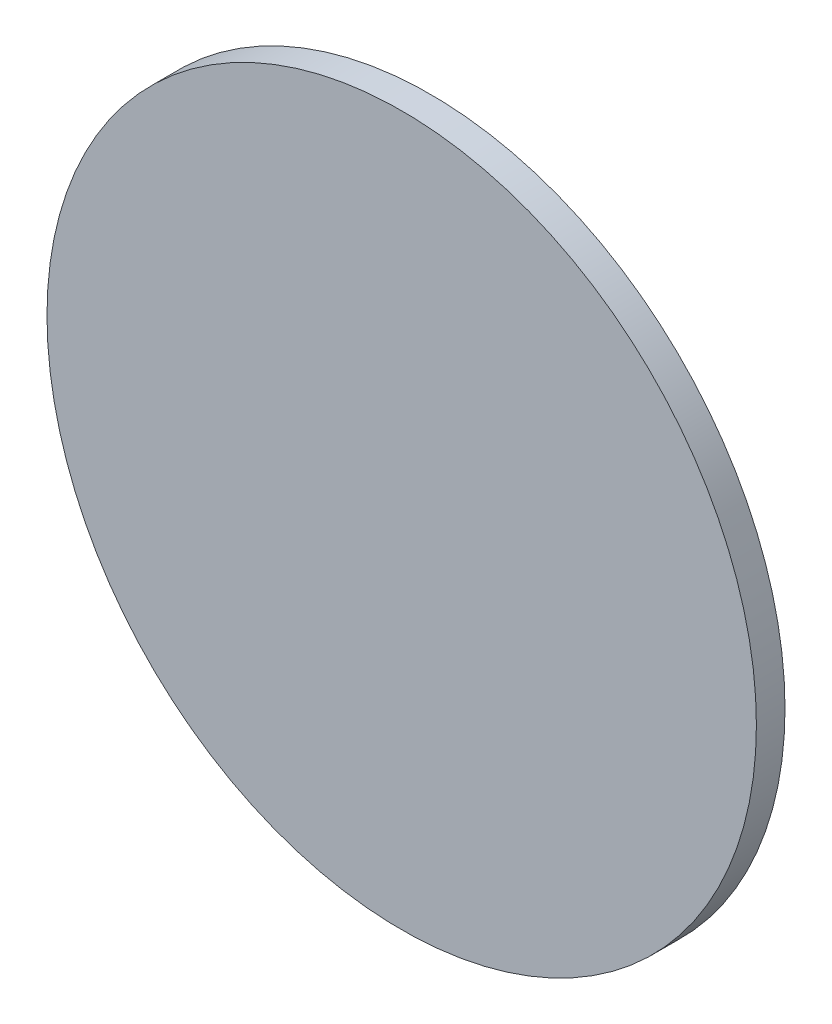
SolidWorks part; units mm, degrees
ref_plane "Front Plane" through (0, 0, 0) normal (0, 0, 1) x (1, 0, 0)
ref_plane "Top Plane" through (0, 0, 0) normal (0, 1, 0) x (1, 0, 0)
ref_plane "Right Plane" through (0, 0, 0) normal (1, 0, 0) x (0, 0, -1)
sketch "Sketch2" plane through (0, 0, 0) normal (0, 1, 0) x (1, 0, 0)
  line L0 (0, 0) -> (0, 5)
  line L1 (0, 5) -> (38.95, 5)
  line L2 (38.95, 5) -> (38.95, 2)
  line L3 (38.95, 2) -> (44.45, 2)
  line L4 (44.45, 2) -> (44.45, 5)
  line L5 (44.45, 5) -> (51, 5)
  line L6 (51, 5) -> (51, 2)
  line L7 (51, 2) -> (57, 2)
  line L8 (57, 2) -> (57, 5)
  line L9 (57, 5) -> (62, 5)
  line L10 (62, 5) -> (62, 0)
  line L11 (62, 0) -> (0, 0)
  line L12 (0, 0) -> (0, -2.4799) construction
  point P14 (60.8357, 0)
  point P16 (69.7281, 0)
  point P17 (76.4544, 0)
  dimension "D1" = 5
  dimension "D2" = 77.9
  dimension "D3" = 88.9
  dimension "D4" = 102
  dimension "D5" = 114
  dimension "D6" = 5
  dimension "D7" = 3
revolve "Revolve1" add sketch "Sketch2" angle 360 about L12
